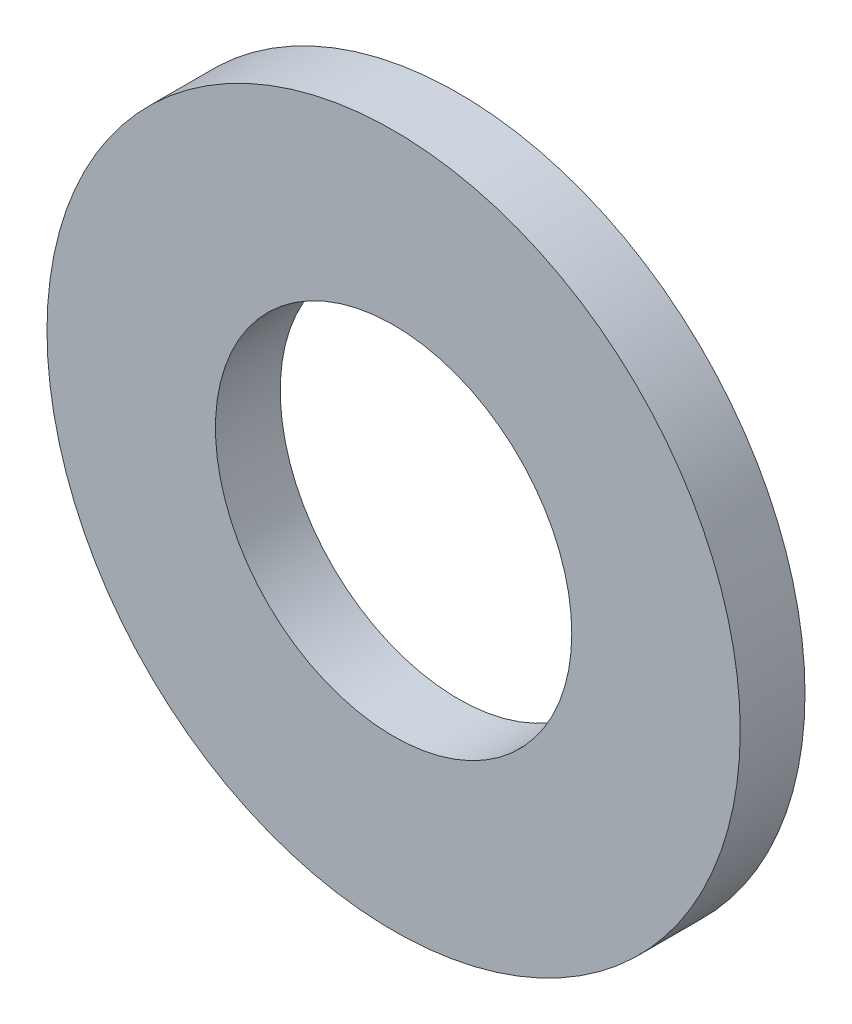
SolidWorks part; units mm, degrees
ref_plane "Front Plane" through (0, 0, 0) normal (0, 0, 1) x (1, 0, 0)
ref_plane "Top Plane" through (0, 0, 0) normal (0, 1, 0) x (1, 0, 0)
ref_plane "Right Plane" through (0, 0, 0) normal (1, 0, 0) x (0, 0, -1)
sketch "Sketch1" plane through (0, 0, 0) normal (0, 0, 1) x (1, 0, 0)
  circle A0 centre (0, 0) radius 2.75
  circle A1 centre (0, 0) radius 5.35
  dimension "D1" = 5.5
  dimension "D2" = 10.7
extrude "Boss-Extrude1" add sketch "Sketch1" along normal blind 1
